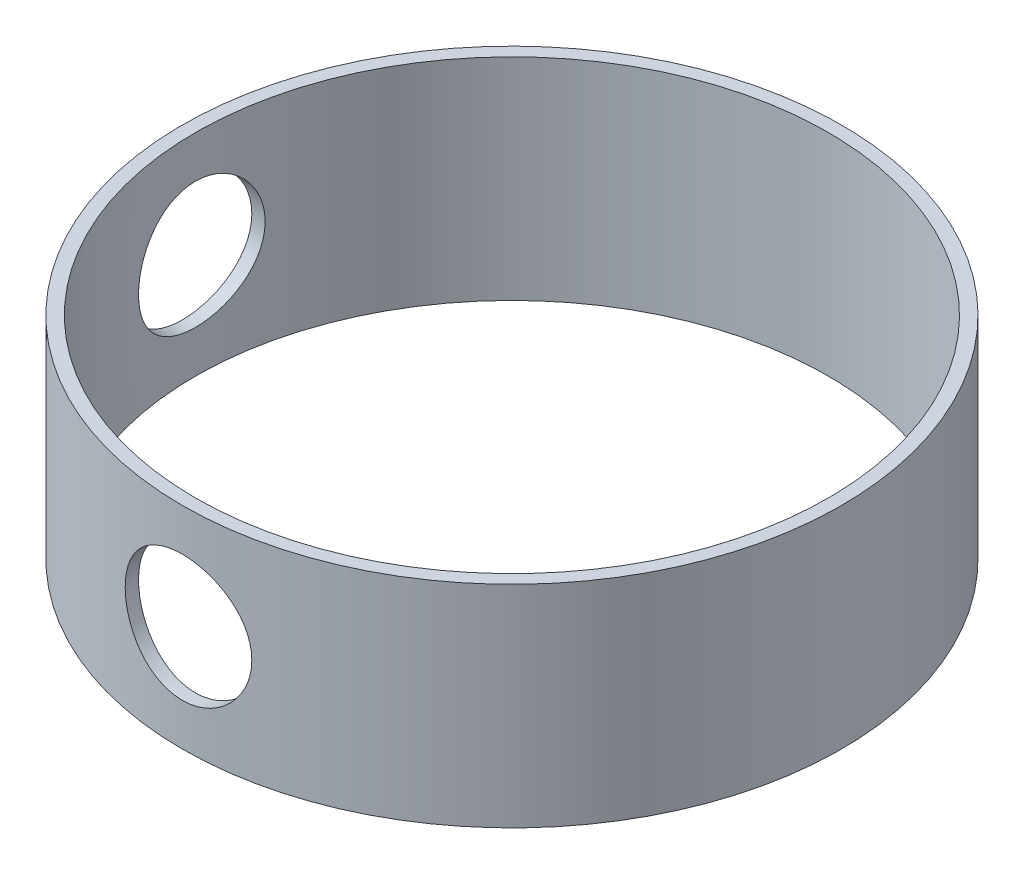
SolidWorks part; units mm, degrees
ref_plane "前视基准面" through (0, 0, 0) normal (0, 0, 1) x (1, 0, 0)
ref_plane "上视基准面" through (0, 0, 0) normal (0, 1, 0) x (1, 0, 0)
ref_plane "右视基准面" through (0, 0, 0) normal (1, 0, 0) x (0, 0, -1)
other "Configuration Table"
sketch "草图1" plane through (0, 0, 0) normal (0, 1, 0) x (1, 0, 0)
  circle A0 centre (0, 0) radius 39.6748
  circle A1 centre (0, 0) radius 38.1
  dimension "D1" = 79.3496
  dimension "D2" = 76.2
extrude "凸台-拉伸1" add sketch "草图1" along normal mid plane 25.4
sketch "Sketch2" plane through (0, 19.05, 0) normal (1, 0, 0) x (0, 0, -1)
  circle A0 centre (0, -19.05) radius 7.62
  dimension "D1" = 15.24
extrude "Cut-Extrude1" cut sketch "Sketch2" against normal through all
pattern_circular "CirPattern1" count 2 over 90 about axis through (0, -12.7, 0) along (0, 1, 0) of "Cut-Extrude1"
equation "\"airframeInnerDiameter\"=3"
equation "\"outerDiameter\"=3.124"
equation "\"airframeBulkheadThickness\"=0.125"
equation "\"payloadAirframeLength\"=5"
equation "\"payloadCouplerInnerDiameter\"=2.88"
equation "\"payloadCouplerLength\"=5.5"
equation "\"payloadCouplerBandLength\"=1"
equation "\"payloadCouplerOuter\"=\"airframeInnerDiameter\""
equation "\"payloadCouplerOffsetFromAft\"=3"
equation "\"upperAirframeLength\"=12.5"
equation "\"recoveryBayInnerDiameter\"=2.88"
equation "\"recoveryBayLength\"=4"
equation "\"recoveryBandLength\"=1"
equation "\"recoveryCouplerOuter\"=\"airframeInnerDiameter\""
equation "\"recoveryOffsetFromAft\"=1.5"
equation "\"midAirframeLength\"=10"
equation "\"ATSBayInnerDiameter\"=2.88"
equation "\"ATSBayLength\"=5.5"
equation "\"ATSBandLength\"=1"
equation "\"ATSCouplerOuter\"=\"airframeInnerDiameter\""
equation "\"ATSOffsetFromAft\"=1.5"
equation "\"lowerAirframeLength\"=20"
equation "\"finSlotLength\"=4.1875"
equation "\"finSlotOffsetFromAft\"=1.5"
equation "\"finSlotWidth\"=0.125"
equation "\"D1@草图1\"=\"outerDiameter\""
equation "\"D2@草图1\"=\"airframeInnerDiameter\""
equation "\"D1@凸台-拉伸1\"=\"payloadCouplerBandLength\""
